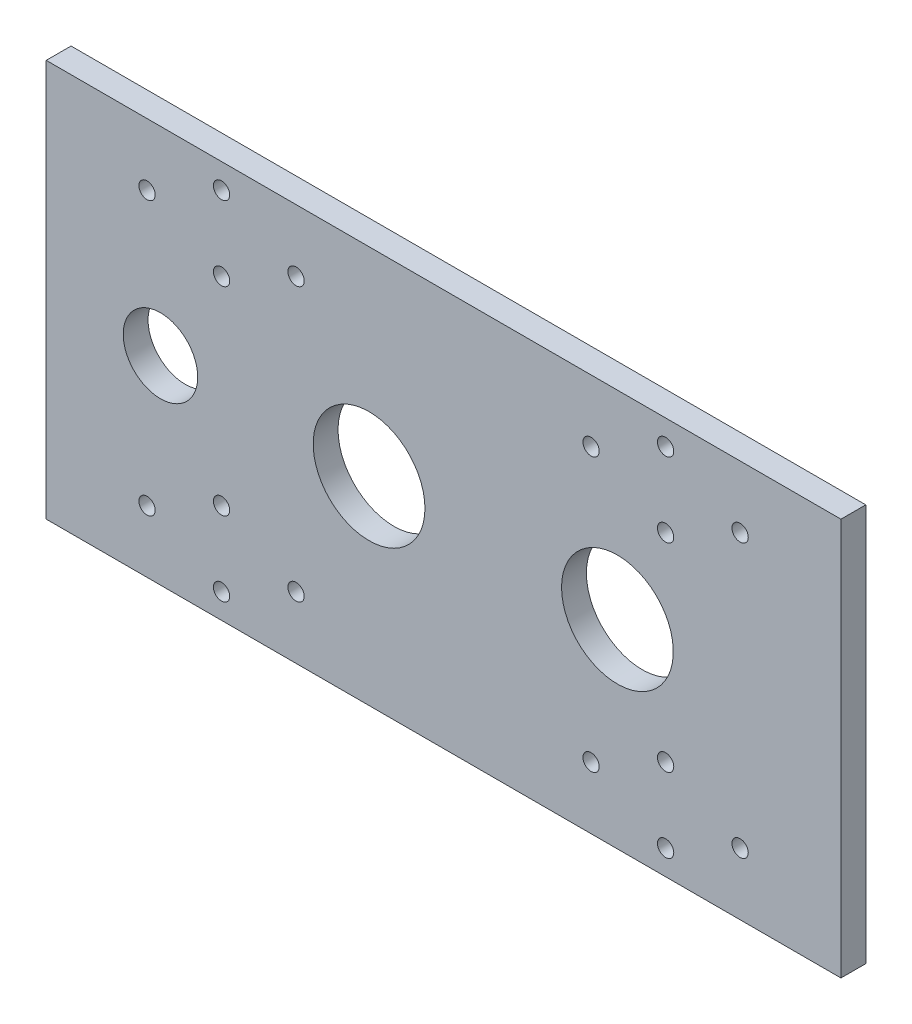
SolidWorks part; units mm, degrees
material "6061 Alloy"
ref_plane "Front Plane" through (0, 0, 0) normal (0, 0, 1) x (1, 0, 0)
ref_plane "Top Plane" through (0, 0, 0) normal (0, 1, 0) x (1, 0, 0)
ref_plane "Right Plane" through (0, 0, 0) normal (1, 0, 0) x (0, 0, -1)
sketch "Sketch1" plane through (0, 0, 0) normal (0, 0, 1) x (1, 0, 0)
  line L1 (0, 0) -> (203.2, 0)
  line L2 (0, 0) -> (0, 101.6)
  line L3 (0, 101.6) -> (203.2, 101.6)
  line L4 (203.2, 0) -> (203.2, 101.6)
  dimension "D1" = 101.6
  dimension "D2" = 203.2
extrude "Boss-Extrude1" add sketch "Sketch1" along normal blind 6.35
sketch "Sketch3" plane through (0, 0, 6.35) normal (0, 0, 1) x (1, 0, 0)
  line L0 (0, 50.8) -> (203.2, 50.8) construction
  line L1 (0, 101.6) -> (0, 0) construction
  line L2 (203.2, 0) -> (203.2, 101.6) construction
  line L3 (101.6, 0) -> (101.6, 101.6) construction
  line L4 (0, 0) -> (203.2, 0) construction
  line L5 (203.2, 101.6) -> (0, 101.6) construction
  circle A0 centre (82.55, 50.8) radius 14.2875
  circle A1 centre (146.05, 50.8) radius 14.2875
  circle A2 centre (29.21, 50.8) radius 9.525
  circle A4 centre (29.21, 50.8) radius 15.24 construction
  circle A5 centre (82.55, 50.8) radius 38.1 construction
  dimension "D1" = 28.575
  dimension "D4" = 19.05
  dimension "D5" = 76.2
  dimension "D6" = 30.48
  dimension "D2" = 63.5
  dimension "D3" = 57.15
extrude "Cut-Extrude2" cut sketch "Sketch3" against normal up to surface (6.35 mm away) up to face at (101.6, 50.8, 0)
sketch "Sketch5" plane through (0, 0, 6.35) normal (0, 0, 1) x (1, 0, 0)
  line L0 (139.319, 85.725) -> (177.419, 85.725) construction
  line L1 (158.369, 95.25) -> (158.369, 76.2) construction
  line L2 (203.2, 0) -> (203.2, 101.6) construction
  line L3 (203.2, 101.6) -> (0, 101.6) construction
  circle A0 centre (139.319, 85.725) radius 2.0828
  circle A1 centre (158.369, 95.25) radius 2.0828
  circle A2 centre (158.369, 76.2) radius 2.0828
  circle A3 centre (177.419, 85.725) radius 2.0828
  point P8 (158.369, 85.725)
  dimension "D5" = 4.1656
  dimension "D1" = 19.05
  dimension "D2" = 38.1
  dimension "D3" = 44.831
  dimension "D4" = 15.875
extrude "Cut-Extrude3" cut sketch "Sketch5" against normal through all
ref_plane "Plane1" through (0, 50.8, 0) normal (0, 1, 0) x (1, 0, 0)
ref_plane "Plane2" through (101.6, 0, 0) normal (1, 0, 0) x (0, 0, -1)
mirror "Mirror1" about plane through (0, 50.8, 0) normal (0, 1, 0) of "Cut-Extrude3"
mirror "Mirror2" about plane through (101.6, 0, 0) normal (1, 0, 0) of "Mirror1", "Cut-Extrude3"
